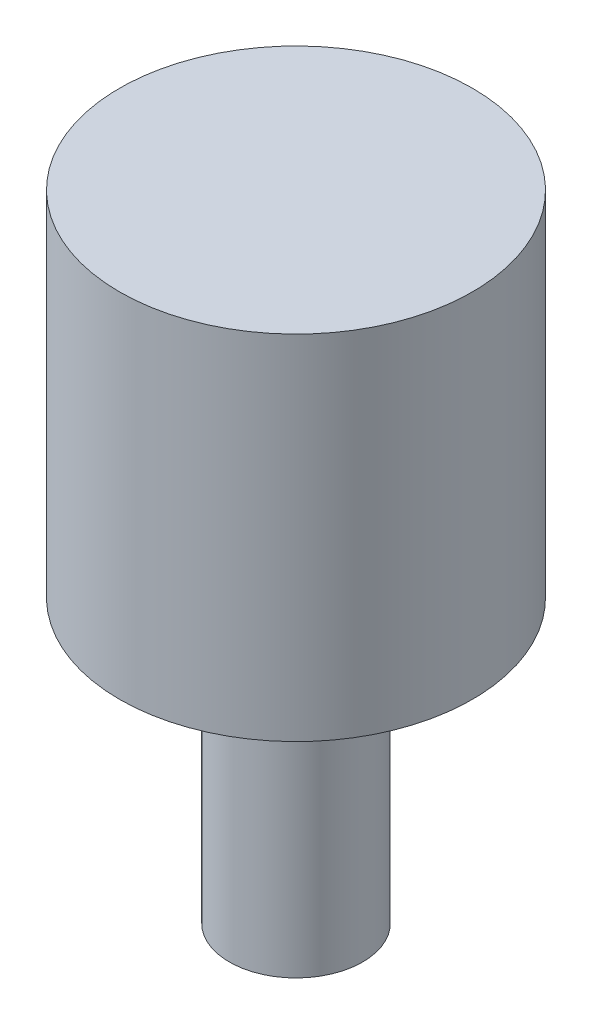
SolidWorks part; units mm, degrees
material "Natural Rubber"
ref_plane "Front Plane" through (0, 0, 0) normal (0, 0, 1) x (1, 0, 0)
ref_plane "Top Plane" through (0, 0, 0) normal (0, 1, 0) x (1, 0, 0)
ref_plane "Right Plane" through (0, 0, 0) normal (1, 0, 0) x (0, 0, -1)
sketch "Sketch2" plane through (0, 0, 0) normal (0, 1, 0) x (1, 0, 0)
  circle A0 centre (0, 0) radius 3.9688
extrude "Boss-Extrude4" add sketch "Sketch2" along normal blind 7.9375
sketch "Sketch4" plane through (0, 0, 0) normal (0, -1, 0) x (1, 0, 0)
  circle A0 centre (0, 0) radius 1.5
extrude "Boss-Extrude5" add sketch "Sketch4" along normal blind 6.35
